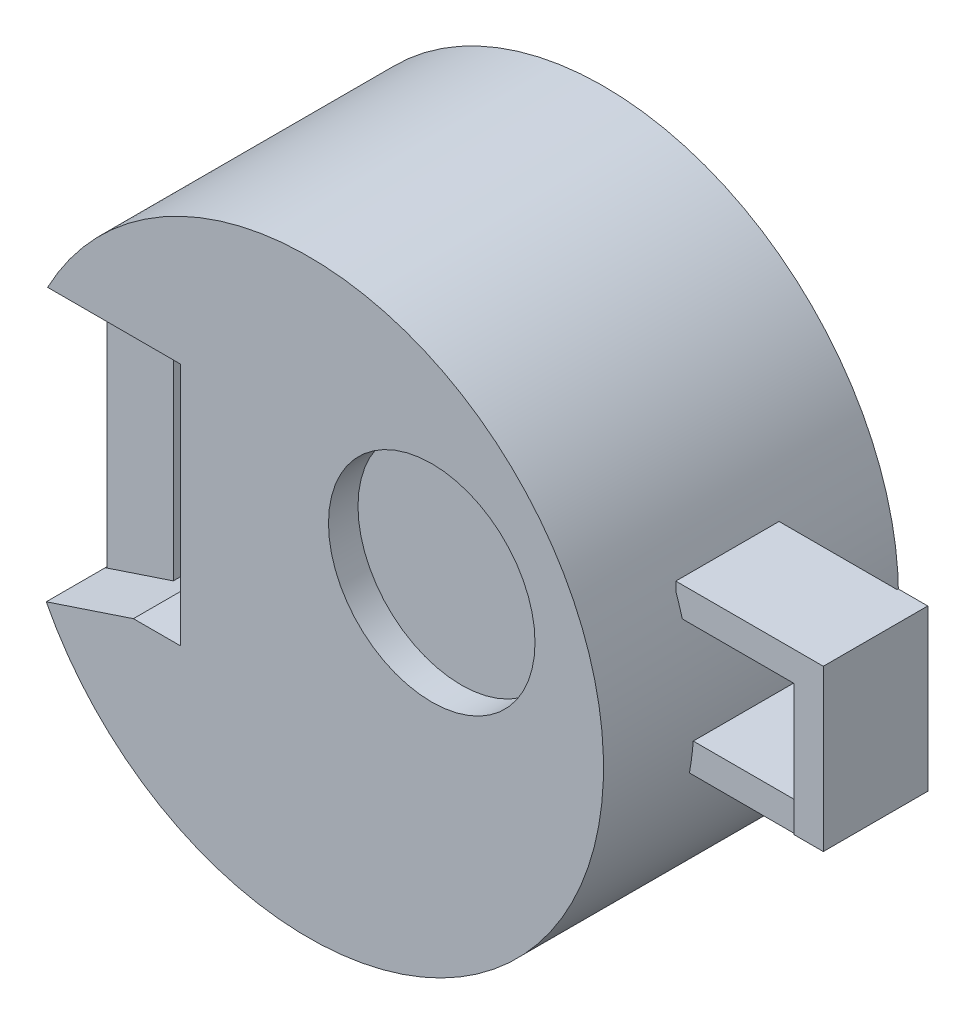
SolidWorks part; units mm, degrees
ref_plane "前基準面" through (0, 0, 0) normal (0, 0, 1) x (1, 0, 0)
ref_plane "上基準面" through (0, 0, 0) normal (0, 1, 0) x (1, 0, 0)
ref_plane "右基準面" through (0, 0, 0) normal (1, 0, 0) x (0, 0, -1)
sketch "草圖1" plane through (0, 0, 0) normal (0, 0, 1) x (1, 0, 0)
  circle A0 centre (0, 0) radius 10
extrude "填料-伸長1" add sketch "草圖1" along normal blind 10 contours A0
sketch "草圖2" plane through (0, 0, 10) normal (0, 0, 1) x (1, 0, 0)
  line L1 (-5.9347, 4.6712) -> (-4.3345, 4.6712)
  line L2 (-5.9347, 4.6712) -> (-5.9347, -3.6)
  line L3 (-5.9347, -3.6) -> (-4.3345, -3.6)
  line L4 (-4.3345, 4.6712) -> (-4.3345, -3.6)
extrude "除料-伸長1" cut sketch "草圖2" against normal blind 10 contours L1 L4 L3 L2
sketch "草圖3" plane through (0, 0, 10) normal (0, 0, 1) x (1, 0, 0)
  line L0 (-5.9347, 4.6712) -> (-8.8419, 4.6712)
  line L1 (-8.8888, -4.5814) -> (-5.9347, -3.6)
  line L2 (-5.9347, -3.6) -> (-5.9347, 4.6712)
  circle A0 centre (0, 0) radius 10 construction
  arc A1 (-8.8419, 4.6712) -> (-8.8888, -4.5814) centre (-2.3388, 0.0118) ccw
extrude "除料-伸長2" cut sketch "草圖3" against normal blind 2 contours L1 L2 L0 A1
sketch "草圖4" plane through (0, 0, 0) normal (0, 0, -1) x (-1, 0, 0)
  line L0 (5.9347, 4.6712) -> (8.8419, 4.6712)
  line L1 (8.8617, -4.6337) -> (5.9347, -4.6337)
  line L2 (5.9347, -4.6337) -> (5.9347, 4.6712)
  circle A0 centre (0, 0) radius 10 construction
  arc A1 (8.8419, 4.6712) -> (8.8617, -4.6337) centre (2.3438, 0.005) cw
extrude "除料-伸長3" cut sketch "草圖4" against normal blind 2
ref_plane "平面1" through (-13.3345, 0, 0) normal (-1, 0, 0) x (0, 0, 1)
sketch "草圖7" plane through (-13.3345, 0, 0) normal (-1, 0, 0) x (0, 0, 1)
  line L0 (2, 4.6712) -> (8, 4.6712)
  line L1 (8, 4.6712) -> (8, -4.5814)
  line L2 (8, -4.5814) -> (2, -4.6337)
  line L3 (2, -4.6337) -> (2, 4.6712)
extrude "除料-伸長4" cut sketch "草圖7" against normal blind 3.5
sketch "草圖9" plane through (0, 0, 8) normal (0, 0, 1) x (1, 0, 0)
  line L0 (-5.9347, 4.6146) -> (-5.9347, -3.6)
  line L1 (-5.9347, -3.6) -> (-5.9347, 4.6712) construction
  line L2 (-8.8888, -4.5814) -> (-5.9347, -3.6) construction
  line L3 (-5.9347, -3.6) -> (-6.5818, -3.815)
  line L4 (-6.5818, -3.815) -> (-6.5818, 4.6146)
  line L5 (-6.5818, 4.6146) -> (-5.9347, 4.6146)
extrude "除料-伸長5" cut sketch "草圖9" against normal blind 8
sketch "草圖16" plane through (-9.8345, 0, 0) normal (-1, 0, 0) x (0, 0, 1)
  line L1 (2, 4.6712) -> (8, 4.6712)
  line L2 (2, 4.6712) -> (2, -4.5814)
  line L3 (2, -4.5814) -> (8, -4.5814)
  line L4 (8, 4.6712) -> (8, -4.5814)
extrude "除料-伸長7" cut sketch "草圖16" against normal blind 1
sketch "草圖17" plane through (0, 0, 0) normal (0, 0, -1) x (-1, 0, 0)
  circle A0 centre (-3.5766, 1.8401) radius 3.5
extrude "除料-伸長8" cut sketch "草圖17" against normal blind 1 contours A0
sketch "草圖18" plane through (0, 0, 10) normal (0, 0, 1) x (1, 0, 0)
  circle A0 centre (4.1776, 2.5076) radius 3.5
extrude "除料-伸長9" cut sketch "草圖18" against normal blind 1 contours A0
ref_plane "平面2" through (9.4182, 0, 0) normal (1, 0, 0) x (0, 0, -1)
sketch "草圖19" plane through (9.4182, 0, 0) normal (1, 0, 0) x (0, 0, -1)
  line L1 (-6.969, 3.6639) -> (-3.469, 3.6639)
  line L2 (-6.969, 3.6639) -> (-6.969, 2.6639)
  line L3 (-6.969, 2.6639) -> (-3.469, 2.6639)
  line L4 (-3.469, 3.6639) -> (-3.469, 2.6639)
  line L5 (-6.969, 3.6639) -> (-3.469, 2.6639) construction
  line L6 (-6.969, 2.6639) -> (-3.469, 3.6639) construction
  point P0 (-5.219, 3.1639)
sketch "草圖20" plane through (9.4182, 0, 0) normal (1, 0, 0) x (0, 0, -1)
  line L1 (-6.929, -0.7759) -> (-3.429, -0.7759)
  line L2 (-6.929, -0.7759) -> (-6.929, -1.7759)
  line L3 (-6.929, -1.7759) -> (-3.429, -1.7759)
  line L4 (-3.429, -0.7759) -> (-3.429, -1.7759)
  line L5 (-6.929, -0.7759) -> (-3.429, -1.7759) construction
  line L6 (-6.929, -1.7759) -> (-3.429, -0.7759) construction
  point P0 (-5.179, -1.2759)
extrude "填料-伸長2" add sketch "草圖19" along normal blind 4 contours L3 L4 L1 L2
extrude "填料-伸長3" add sketch "草圖20" along normal blind 4 contours L3 L4 L1 L2
sketch "草圖21" plane through (13.4182, 0, 0) normal (1, 0, 0) x (0, 0, -1)
  line L1 (-6.969, 3.6639) -> (-3.429, 3.6639)
  line L2 (-6.969, 3.6639) -> (-6.969, -1.7759)
  line L3 (-6.969, -1.7759) -> (-3.429, -1.7759)
  line L4 (-3.429, 3.6639) -> (-3.429, -1.7759)
extrude "填料-伸長4" add sketch "草圖21" along normal blind 1 contours L4 L3 L2 L1
